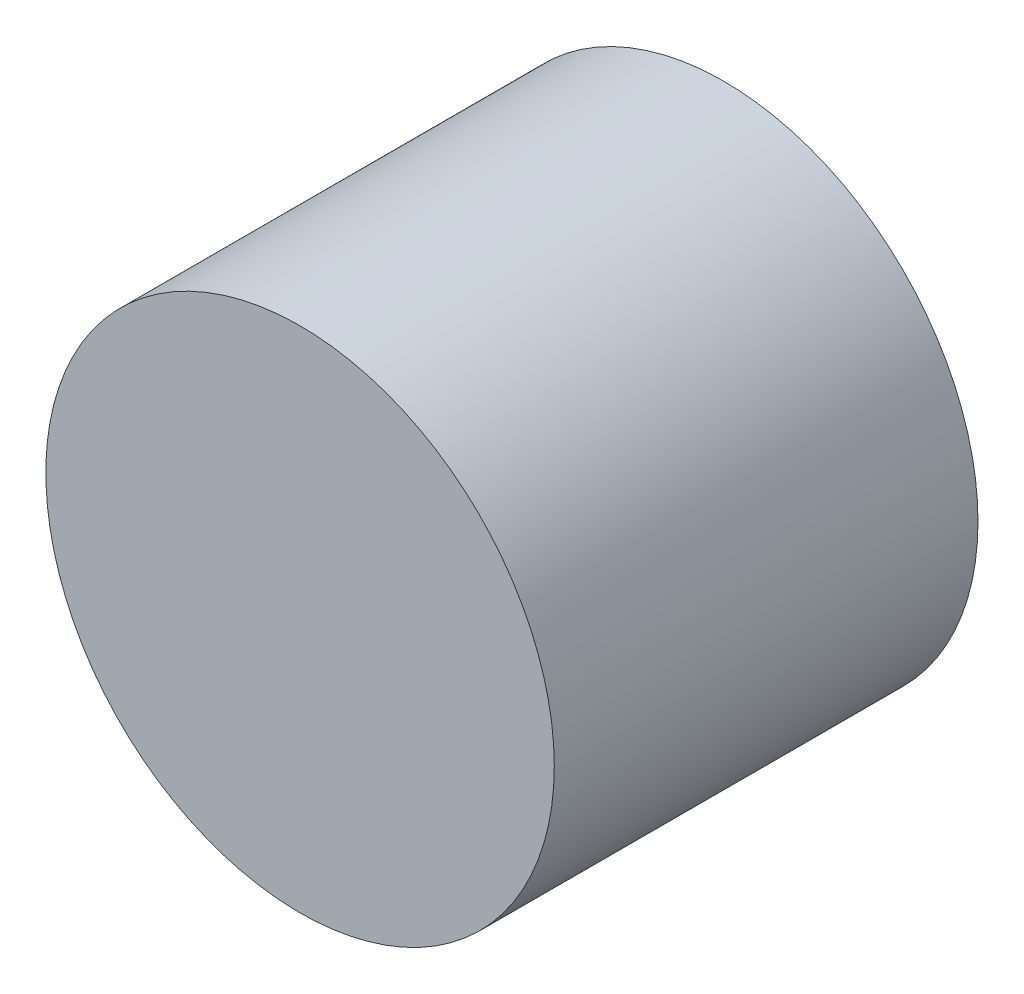
SolidWorks part; units mm, degrees
ref_plane "Спереди" through (0, 0, 0) normal (0, 0, 1) x (1, 0, 0)
ref_plane "Сверху" through (0, 0, 0) normal (0, 1, 0) x (1, 0, 0)
ref_plane "Справа" through (0, 0, 0) normal (1, 0, 0) x (0, 0, -1)
other "Configuration Table"
sketch "Эскиз1" plane through (0, 0, 0) normal (0, 0, 1) x (1, 0, 0)
  circle A0 centre (0, 0) radius 30
  dimension "D1" = 60
extrude "Бобышка-Вытянуть1" add sketch "Эскиз1" along normal blind 50
